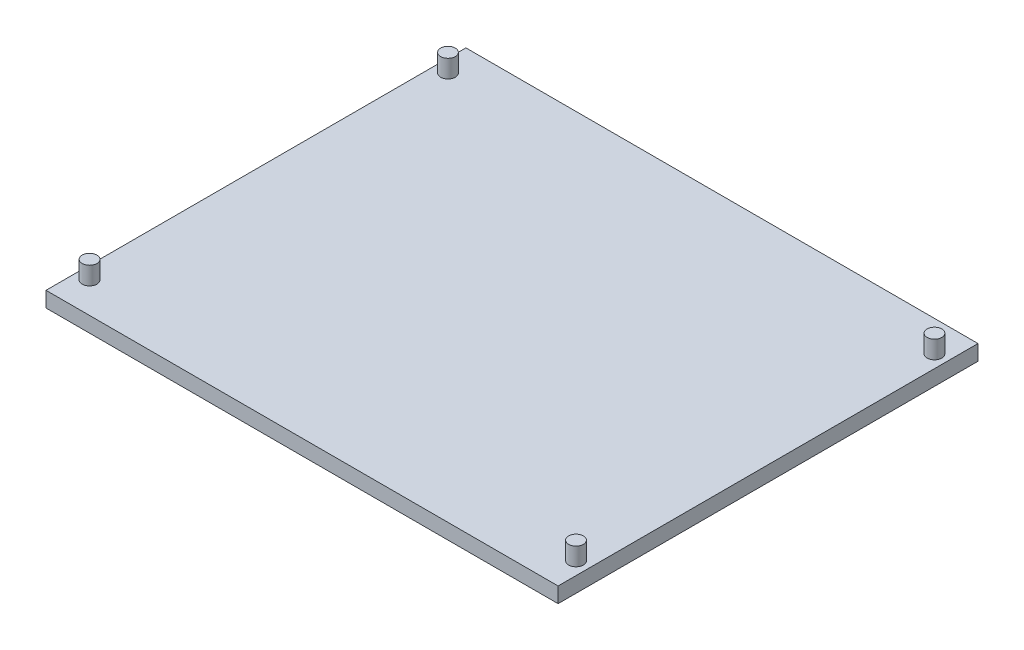
SolidWorks part; units mm, degrees
ref_plane "Front Plane" through (0, 0, 0) normal (0, 0, 1) x (1, 0, 0)
ref_plane "Top Plane" through (0, 0, 0) normal (0, 1, 0) x (1, 0, 0)
ref_plane "Right Plane" through (0, 0, 0) normal (1, 0, 0) x (0, 0, -1)
sketch "Sketch1" plane through (0, 0, 0) normal (0, 1, 0) x (1, 0, 0)
  line L1 (-50, -41) -> (50, -41)
  line L2 (-50, -41) -> (-50, 41)
  line L3 (-50, 41) -> (50, 41)
  line L4 (50, -41) -> (50, 41)
  line L5 (-50, -41) -> (50, 41) construction
  line L6 (-50, 41) -> (50, -41) construction
  point P0 (0, 0)
  dimension "D1" = 100
  dimension "D2" = 82
extrude "Boss-Extrude1" add sketch "Sketch1" along normal blind 3
sketch "Sketch4" plane through (0, 3, 0) normal (0, 1, 0) x (1, 0, 0)
  line L0 (-50, 41) -> (-47.5, 41) construction
  line L1 (50, 41) -> (-50, 41) construction
  line L2 (-47.5, 41) -> (-47.5, 35) construction
  line L3 (0, -1.65) -> (0, 1.65) construction
  line L4 (-1.65, 0) -> (1.65, 0) construction
  circle A0 centre (-47.5, 35) radius 1.435
  circle A1 centre (47.5, 35) radius 1.435
  circle A2 centre (47.5, -35) radius 1.435
  circle A3 centre (-47.5, -35) radius 1.435
  dimension "D3" = 2.87
  dimension "D1" = 2.5
  dimension "D2" = 6
extrude "Boss-Extrude2" add sketch "Sketch4" along normal blind 3.5
